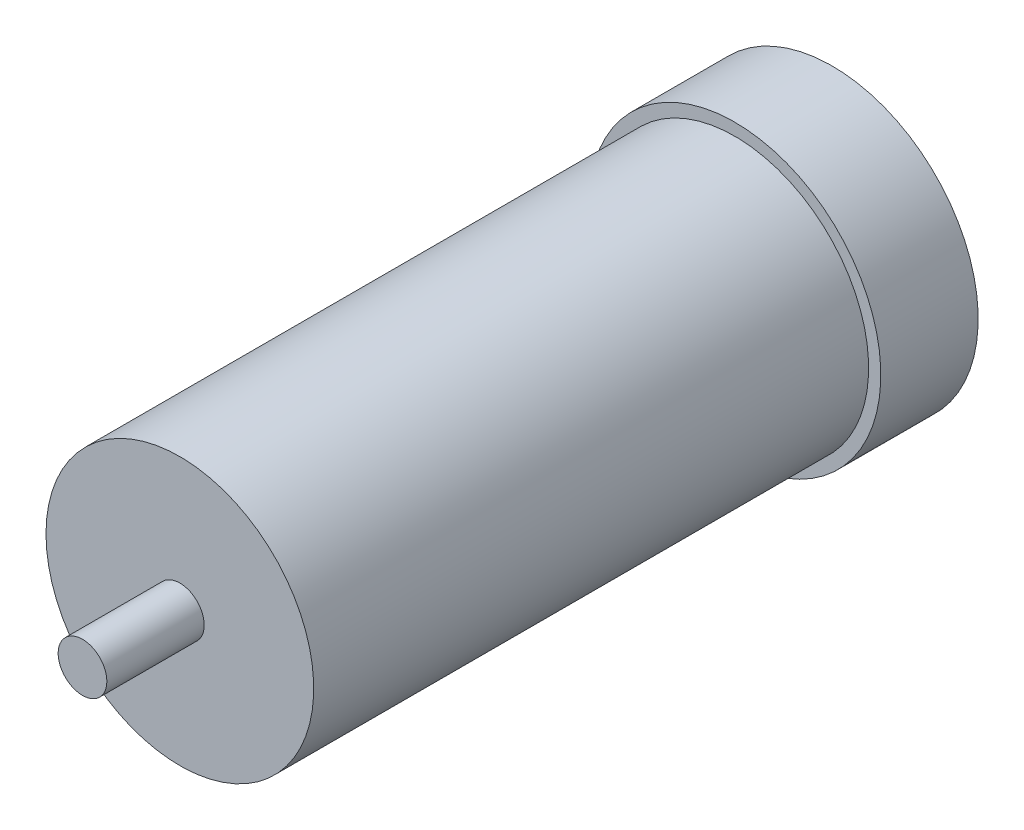
SolidWorks part; units mm, degrees
ref_plane "Front Plane" through (0, 0, 0) normal (0, 0, 1) x (1, 0, 0)
ref_plane "Top Plane" through (0, 0, 0) normal (0, 1, 0) x (1, 0, 0)
ref_plane "Right Plane" through (0, 0, 0) normal (1, 0, 0) x (0, 0, -1)
sketch "Sketch1" plane through (0, 0, 0) normal (0, 0, 1) x (1, 0, 0)
  circle A0 centre (0, 0) radius 27.5
  dimension "D1" = 55
extrude "Boss-Extrude1" add sketch "Sketch1" along normal blind 114
sketch "Sketch2" plane through (0, 0, 0) normal (0, 0, -1) x (-1, 0, 0)
  circle A0 centre (0, 0) radius 30
  dimension "D1" = 60
extrude "Boss-Extrude2" add sketch "Sketch2" along normal blind 20
sketch "Sketch3" plane through (0, 0, 114) normal (0, 0, 1) x (1, 0, 0)
  circle A0 centre (0, 0) radius 5
  dimension "D1" = 10
extrude "Boss-Extrude3" add sketch "Sketch3" along normal blind 20
